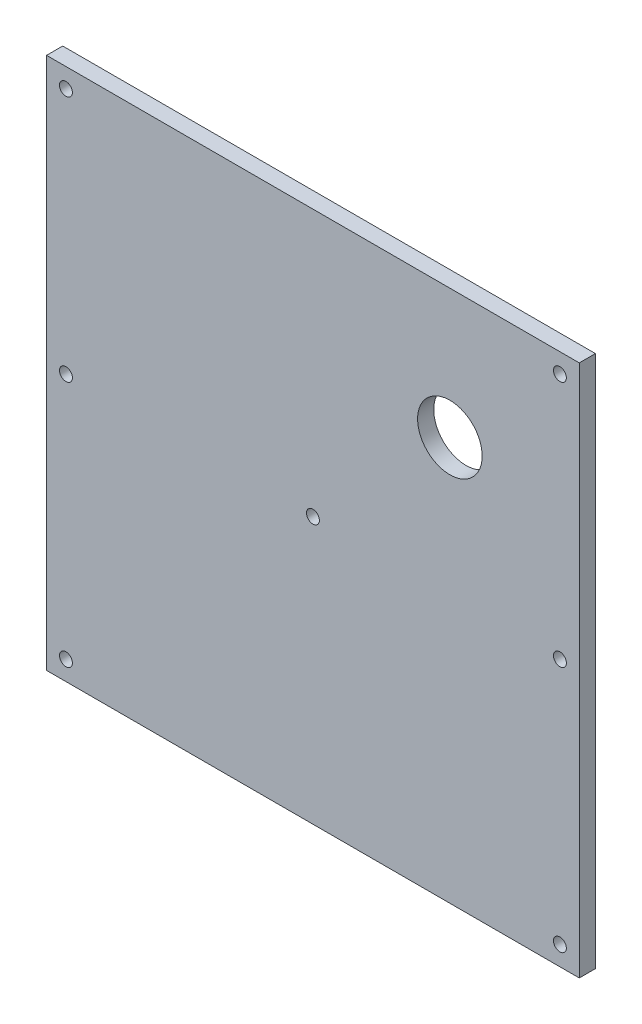
SolidWorks part; units mm, degrees
ref_plane "Plan de face" through (0, 0, 0) normal (0, 0, 1) x (1, 0, 0)
ref_plane "Plan de dessus" through (0, 0, 0) normal (0, 1, 0) x (1, 0, 0)
ref_plane "Plan de droite" through (0, 0, 0) normal (1, 0, 0) x (0, 0, -1)
sketch "Esquisse1" plane through (0, 0, 0) normal (0, 0, 1) x (1, 0, 0)
  line L1 (-82.5, -82.5) -> (82.5, -82.5)
  line L2 (-82.5, -82.5) -> (-82.5, 82.5)
  line L3 (-82.5, 82.5) -> (82.5, 82.5)
  line L4 (82.5, -82.5) -> (82.5, 82.5)
  line L5 (-82.5, -82.5) -> (82.5, 82.5) construction
  line L6 (-82.5, 82.5) -> (82.5, -82.5) construction
  circle A6 centre (-76.5, 76.5) radius 2
  circle A7 centre (-76.5, 0) radius 2
  circle A8 centre (-76.5, -76.5) radius 2
  circle A9 centre (76.5, -76.5) radius 2
  circle A10 centre (76.5, 0) radius 2
  circle A11 centre (76.5, 76.5) radius 2
  circle A13 centre (0, 0) radius 2
  circle A14 centre (42.4169, 42.4434) radius 10
  point P0 (0, 0)
  point P30 (42.4169, 42.4434)
  dimension "D1" = 20
extrude "Boss.-Extru.1" add sketch "Esquisse1" along normal blind 5
sketch "Esquisse2" plane through (0, 0, 0) normal (0, 0, -1) x (-1, 0, 0)
  line L0 (4, 77.5) -> (4, 6.3443)
  line L1 (-4, 77.1439) -> (-4, 6.3443)
  line L2 (4, 77.5) -> (2, 77.4914)
  line L3 (2, 72.5) -> (-2, 72.5)
  line L4 (-2, 77.1439) -> (-2, 72.5)
  line L5 (-2, 77.1439) -> (-4, 77.1439)
  line L6 (2, 77.4914) -> (2, 72.5)
  line L7 (0, -0.9455) -> (0, 80.2954) construction
  line L8 (2, 12.2284) -> (-2, 12.2284)
  line L9 (2, 12.2284) -> (2, 7.2284)
  line L10 (-2, 12.2284) -> (-2, 7.2284)
  arc A0 (4, 6.3443) -> (2, 7.2284) centre (0, 0) ccw
  arc A1 (-2, 7.2284) -> (-4, 6.3443) centre (0, 0) ccw
  dimension "D1" = 2
  dimension "D2" = 2
  dimension "D3" = 2
  dimension "D4" = 2
extrude "Boss.-Extru.2" add sketch "Esquisse2" along normal blind 5
